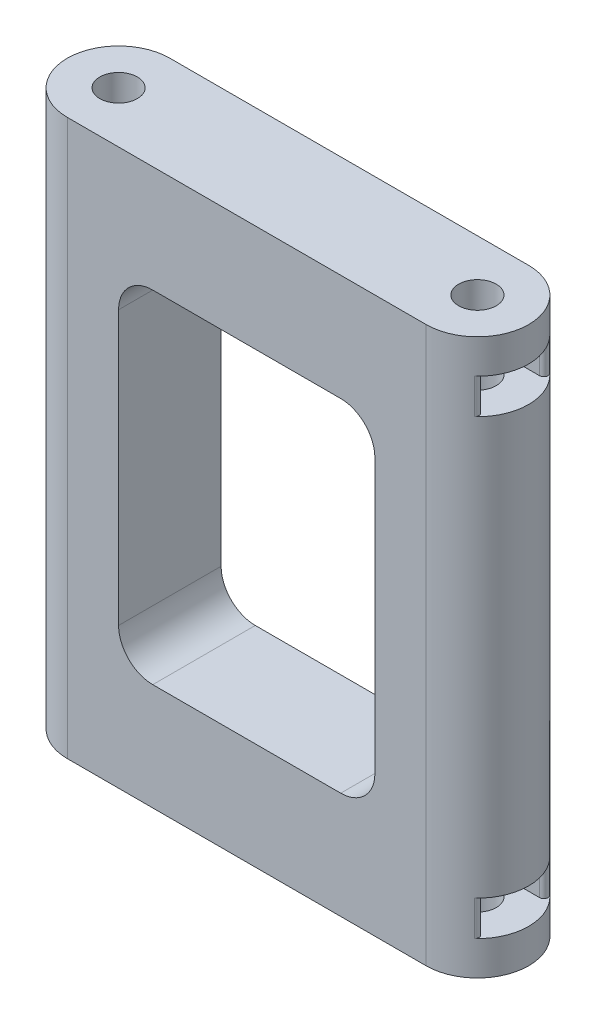
SolidWorks part; units mm, degrees
ref_plane "Front Plane" through (0, 0, 0) normal (0, 0, 1) x (1, 0, 0)
ref_plane "Top Plane" through (0, 0, 0) normal (0, 1, 0) x (1, 0, 0)
ref_plane "Right Plane" through (0, 0, 0) normal (1, 0, 0) x (0, 0, -1)
sketch "Sketch1" plane through (0, 0, 0) normal (0, 1, 0) x (1, 0, 0)
  line L0 (0, 0) -> (42, 0) construction
  line L1 (0, 6) -> (42, 6)
  line L2 (0, -6) -> (42, -6)
  arc A0 (0, 6) -> (0, -6) centre (0, 0) ccw
  arc A1 (42, -6) -> (42, 6) centre (42, 0) ccw
  circle A2 centre (0, 0) radius 2.2
  circle A3 centre (42, 0) radius 2.2
  point P3 (21, 0)
  dimension "D2" = 6
  dimension "D3" = 4.4
  dimension "D4" = 4.4
  dimension "D1" = 42
extrude "Boss-Extrude1" add sketch "Sketch1" along normal blind 65
ref_plane "Plane1" through (0, 61, 0) normal (0, 1, 0) x (1, 0, 0)
sketch "Sketch3" plane through (0, 61, 0) normal (0, 1, 0) x (1, 0, 0)
  line L0 (21, 6) -> (21, 14.1583) construction
  line L1 (4.0992, 0) -> (2.0496, 3.55)
  line L2 (2.0496, 3.55) -> (-9.0461, 3.55)
  line L5 (-8.518, -3.55) -> (2.0496, -3.55)
  line L6 (2.0496, -3.55) -> (4.0992, 0)
  line L7 (42, 6) -> (0, 6) construction
  line L8 (-9.0461, 3.55) -> (-8.518, -3.55)
  line L9 (-1.9873, 3.6578) -> (-4.0355, 0.1102) [skipped]
  line L10 (-4.1614, 0.1078) -> (-2.1132, -3.4398) [skipped]
  line L11 (39.9504, 3.55) -> (51.0461, 3.55)
  line L12 (37.9008, 0) -> (39.9504, 3.55)
  line L13 (39.9504, -3.55) -> (37.9008, 0)
  line L14 (50.518, -3.55) -> (39.9504, -3.55)
  line L15 (51.0461, 3.55) -> (50.518, -3.55)
  circle A0 centre (0, 0) radius 3.55 construction
  dimension "D1" = 7.1
extrude "Cut-Extrude1" cut sketch "Sketch3" against normal blind 4.1
fillet "Fillet1" radius 0.5 4 edges at (46.8371, 58.95, -3.55) (46.8371, 58.95, 3.55) (-4.8371, 58.95, -3.55) (-4.8371, 58.95, 3.55)
ref_plane "Plane2" through (0, 32.5, 0) normal (0, 1, 0) x (1, 0, 0)
mirror "Mirror1" about plane through (0, 32.5, 0) normal (0, 1, 0) of "Fillet1", "Cut-Extrude1"
sketch "Sketch4" plane through (0, 0, -6) normal (0, 0, -1) x (-1, 0, 0)
  line L0 (-21, 0) -> (-21, 65) construction
  line L1 (-42, 0) -> (0, 0) construction
  line L2 (-42, 65) -> (0, 65) construction
  line L4 (-36, 12.5) -> (-6, 12.5)
  line L5 (-36, 12.5) -> (-36, 52.5)
  line L6 (-36, 52.5) -> (-6, 52.5)
  line L7 (-6, 12.5) -> (-6, 52.5)
  line L8 (-36, 12.5) -> (-6, 52.5) construction
  line L9 (-36, 52.5) -> (-6, 12.5) construction
  point P8 (-21, 32.5)
  dimension "D1" = 30
  dimension "D2" = 40
extrude "Cut-Extrude2" cut sketch "Sketch4" against normal through all
fillet "Fillet2" radius 4 4 edges at (36, 12.5, 0) (6, 12.5, 0) (6, 52.5, 0) (36, 52.5, 0)
